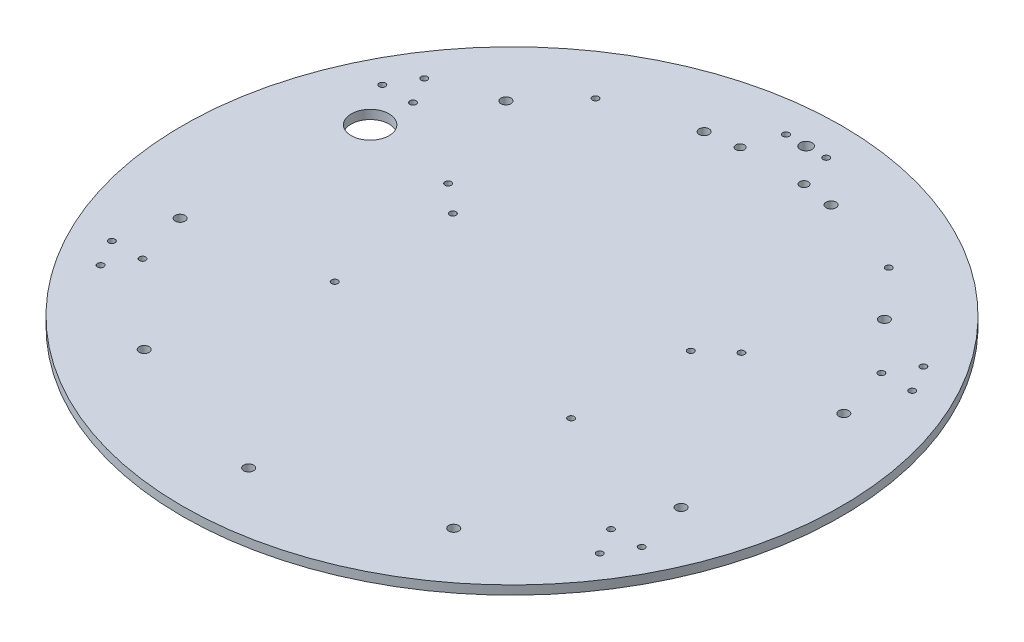
SolidWorks part; units mm, degrees
ref_plane "Front Plane" through (0, 0, 0) normal (0, 0, 1) x (1, 0, 0)
ref_plane "Top Plane" through (0, 0, 0) normal (0, 1, 0) x (1, 0, 0)
ref_plane "Right Plane" through (0, 0, 0) normal (1, 0, 0) x (0, 0, -1)
sketch "Sketch1" plane through (0, 0, 0) normal (0, 1, 0) x (1, 0, 0)
  circle A0 centre (0, 0) radius 177
  dimension "D1" = 354
extrude "Plate" add sketch "Sketch1" along normal blind 4.7625
sketch "Sketch2" plane through (0, 4.7625, 0) normal (0, 1, 0) x (1, 0, 0)
  line L1 (-177, 0) -> (177, 0) construction
  line L2 (0, -177) -> (0, 177) construction
  circle A65 centre (0, 0) radius 177 construction
  circle A69 centre (134.0391, -86.9125) radius 1.7
  circle A71 centre (125.7902, -72.625) radius 1.7
  circle A73 centre (142.288, -72.625) radius 1.7
  circle A83 centre (-142.288, -72.625) radius 1.7
  circle A84 centre (-125.7902, -72.625) radius 1.7
  circle A85 centre (-134.0391, -86.9125) radius 1.7
  circle A86 centre (-134.0391, 86.9125) radius 1.7
  circle A87 centre (-125.7902, 72.625) radius 1.7
  circle A88 centre (-142.288, 72.625) radius 1.7
  circle A89 centre (142.288, 72.625) radius 1.7
  circle A90 centre (125.7902, 72.625) radius 1.7
  circle A91 centre (134.0391, 86.9125) radius 1.7
  point P13 (134.0391, -77.3875)
  point P32 (134.0391, -77.3875)
  point P36 (0, 0)
  dimension "D3" = 3.4
extrude "Standoffs" cut sketch "Sketch2" against normal through all
sketch "Sketch3" plane through (0, 4.7625, 0) normal (0, 1, 0) x (1, 0, 0)
  line L0 (-177, 0) -> (177, 0) construction
  line L1 (0, -177) -> (0, 177) construction
  circle A0 centre (64.2765, 31.75) radius 1.7
  circle A1 centre (-63.5, 31.75) radius 1.7
  circle A2 centre (-63.5, -31.75) radius 1.7
  circle A3 centre (63.5, -31.7453) radius 1.7
  circle A4 centre (0, 0) radius 177 construction
  dimension "D1" = 3.4
  dimension "D2" = 3.4
  dimension "D3" = 3.4
  dimension "D4" = 3.4
  dimension "D9" = 31.75
  dimension "D10" = 0
  dimension "D11" = 0
  dimension "D12" = 63.5
  dimension "D6" = 31.75
  dimension "D5" = 63.5
  dimension "D7" = 63.5
  dimension "D8" = 63.5
extrude "LIDAR" cut sketch "Sketch3" against normal through all
sketch "Sketch4" plane through (0, 4.7625, 0) normal (0, 1, 0) x (1, 0, 0)
  circle A0 centre (-17.145, 139.7) radius 2.286
  circle A1 centre (17.145, 139.7) radius 2.286
  dimension "D1" = 4.572
  dimension "D2" = 4.572
  dimension "D6" = 17.145
  dimension "D3" = 0
  dimension "D4" = 34.29
  dimension "D5" = 139.7
extrude "Camera" cut sketch "Sketch4" against normal through all
sketch "Sketch5" plane through (0, 4.7625, 0) normal (0, 1, 0) x (1, 0, 0)
  line L0 (0, 0) -> (0, 205.9566) construction
  line L1 (-177, 0) -> (177, 0) construction
  circle A0 centre (78.745, 123.61) radius 1.7
  circle A1 centre (-78.745, 123.61) radius 1.7
  circle A2 centre (78.745, 44.45) radius 1.7
  circle A3 centre (-78.745, 44.45) radius 1.7
  circle A4 centre (0, 0) radius 177 construction
  dimension "D1" = 3.4
  dimension "D2" = 3.4
  dimension "D3" = 3.4
  dimension "D4" = 3.4
  dimension "D9" = 78.745
  dimension "D11" = 44.45
  dimension "D5" = 157.49
  dimension "D6" = 157.49
  dimension "D7" = 79.16
  dimension "D8" = 79.16
  dimension "D10" = 78.745
  dimension "D12" = 44.45
extrude "Display" cut sketch "Sketch5" against normal through all
sketch "Sketch6" plane through (0, 4.7625, 0) normal (0, 1, 0) x (1, 0, 0)
  circle A0 centre (-127, 50.8) radius 10.16
  dimension "D1" = 20.32
  dimension "D3" = 50.8
  dimension "D2" = 127
extrude "Wires" cut sketch "Sketch6" against normal through all
sketch "Sketch7" plane through (0, 4.7625, 0) normal (0, 1, 0) x (1, 0, 0)
  line L0 (0, 0) -> (0, 177) construction
  line L1 (-63.1729, 157.95) -> (56.1499, 157.95) construction
  circle A0 centre (0, 157.95) radius 3.175
  circle A1 centre (0, 0) radius 177 construction
  circle A2 centre (-10.795, 157.95) radius 1.7
  circle A3 centre (10.795, 157.95) radius 1.7
  dimension "D1" = 6.35
  dimension "D3" = 3.4
  dimension "D4" = 3.4
  dimension "D6" = 10.795
  dimension "D2" = 19.05
  dimension "D5" = 10.795
extrude "Arducam" cut sketch "Sketch7" against normal through all
sketch "Sketch8" plane through (0, 4.7625, 0) normal (0, 1, 0) x (1, 0, 0)
  line L0 (0, 177) -> (0, -177) construction
  circle A0 centre (0, -141.44) radius 2.667
  circle A1 centre (0, 0) radius 177 construction
  circle A2 centre (-83.1363, -114.4274) radius 2.667
  circle A3 centre (-134.5174, -43.7074) radius 2.667
  circle A8 centre (134.5174, 43.7074) radius 2.667
  circle A9 centre (134.5174, -43.7074) radius 2.667
  circle A10 centre (83.1363, -114.4274) radius 2.667
  circle A11 centre (-83.1363, 114.4274) radius 2.667 [skipped]
  circle A12 centre (0, 141.44) radius 2.667 [skipped]
  circle A13 centre (83.1363, 114.4274) radius 2.667 [skipped]
  circle A14 centre (-134.5174, 43.7074) radius 2.667 [skipped]
  circle A15 centre (-101.628, 98.3718) radius 2.667
  circle A16 centre (-34.1005, 137.2677) radius 2.667
  circle A17 centre (101.628, 98.3718) radius 2.667
  circle A18 centre (34.1005, 137.2677) radius 2.667
  point P29 (0, 0)
  dimension "D1" = 10
  dimension "D2" = 5.334
  dimension "D3" = 5.334
  dimension "D4" = 35.56
  dimension "D6" = 5.334
  dimension "D5" = 141.44
  dimension "D7" = 141.44
extrude "Ziptie" cut sketch "Sketch8" against normal through all and the other way through all
